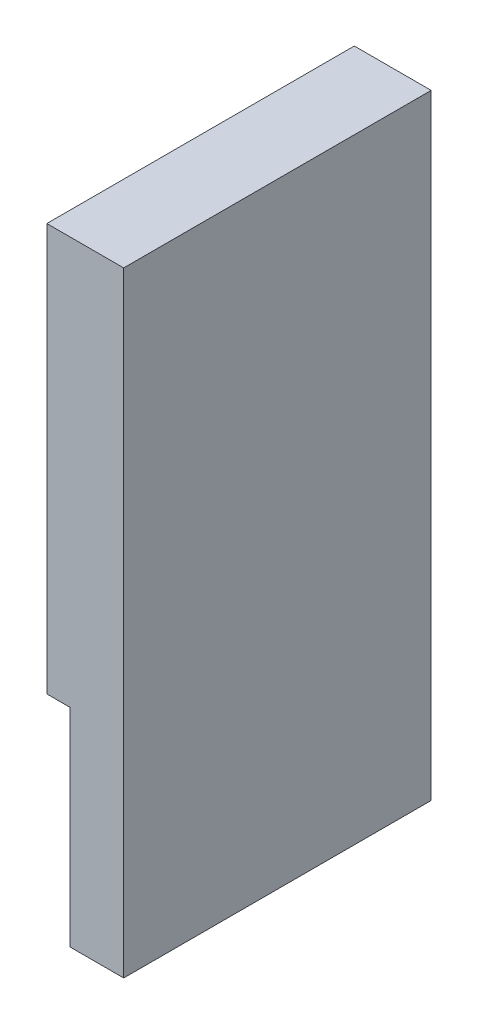
SolidWorks part; units mm, degrees
ref_plane "Front Plane" through (0, 0, 0) normal (0, 0, 1) x (1, 0, 0)
ref_plane "Top Plane" through (0, 0, 0) normal (0, 1, 0) x (1, 0, 0)
ref_plane "Right Plane" through (0, 0, 0) normal (1, 0, 0) x (0, 0, -1)
sketch "Sketch1" plane through (0, 0, 0) normal (1, 0, 0) x (0, 0, -1)
  line L1 (0, 81.8391) -> (40, 81.8391)
  line L2 (0, 81.8391) -> (0, 1.8391)
  line L3 (0, 1.8391) -> (40, 1.8391)
  line L4 (40, 81.8391) -> (40, 1.8391)
  dimension "D1" = 40
  dimension "D2" = 80
extrude "Boss-Extrude1" add sketch "Sketch1" along normal blind 10
sketch "Sketch2" plane through (0, 0, 0) normal (-1, 0, 0) x (0, 0, 1)
  line L0 (-40, 1.8391) -> (-40, 81.8391) construction
  line L1 (-40, 28.8391) -> (0, 28.8391)
  line L2 (-40, 28.8391) -> (-40, 1.8391)
  line L3 (-40, 1.8391) -> (0, 1.8391)
  line L4 (0, 28.8391) -> (0, 1.8391)
  dimension "D1" = 27
extrude "Cut-Extrude1" cut sketch "Sketch2" against normal blind 3
